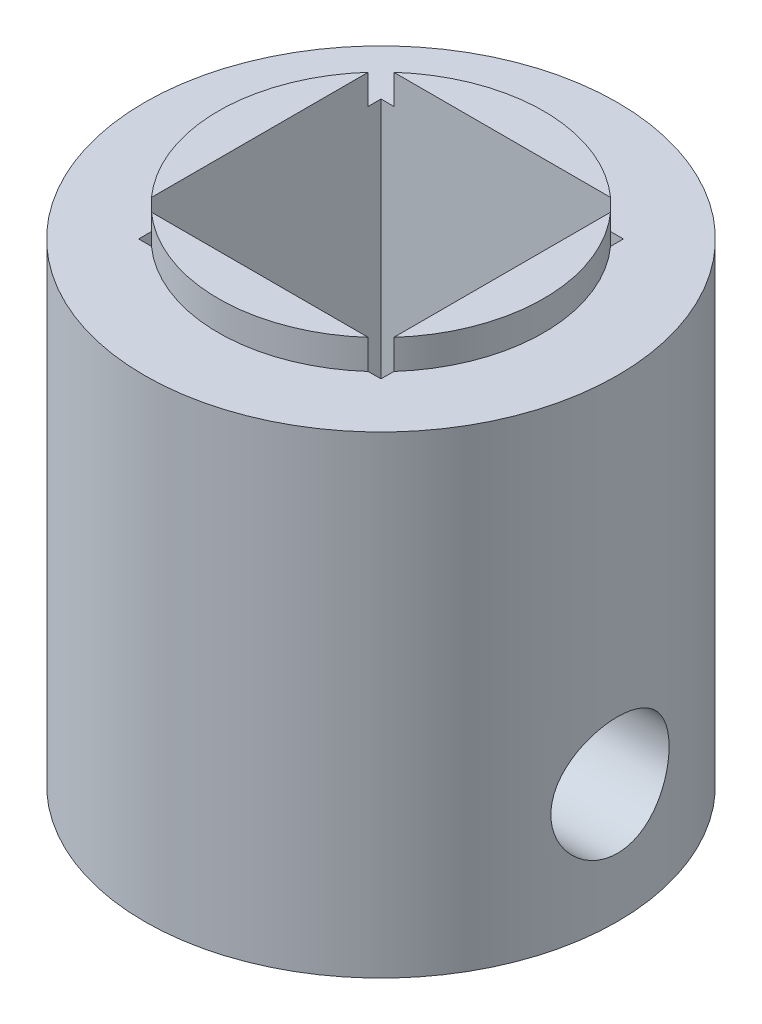
SolidWorks part; units mm, degrees
ref_plane "Front" through (0, 0, 0) normal (0, 0, 1) x (1, 0, 0)
ref_plane "Top" through (0, 0, 0) normal (0, 1, 0) x (1, 0, 0)
ref_plane "Right" through (0, 0, 0) normal (1, 0, 0) x (0, 0, -1)
sketch "Sketch1" plane through (0, 0, 0) normal (0, 1, 0) x (1, 0, 0)
  circle A0 centre (0, 0) radius 5.5
extrude "Boss-Extrude1" add sketch "Sketch1" along normal blind 1
sketch "Sketch2" plane through (0, 0, 0) normal (0, -1, 0) x (-1, 0, 0)
  circle A0 centre (0, 0) radius 8
extrude "Boss-Extrude2" add sketch "Sketch2" along normal blind 16
sketch "Sketch3" plane through (0, -16, 0) normal (0, -1, 0) x (1, 0, 0)
  line L1 (4.1, -4.1) -> (-4.1, -4.1)
  line L2 (4.1, -4.1) -> (4.1, 4.1)
  line L3 (4.1, 4.1) -> (-4.1, 4.1)
  line L4 (-4.1, -4.1) -> (-4.1, 4.1)
  line L5 (4.1, -4.1) -> (-4.1, 4.1) construction
  line L6 (4.1, 4.1) -> (-4.1, -4.1) construction
  point P0 (0, 0)
  dimension "D1" = 8.2
  dimension "D2" = 8.2
extrude "Cut-Extrude1" cut sketch "Sketch3" against normal through all
ref_plane "Plane1" through (-8, 0, 0) normal (-1, 0, 0) x (0, 0, 1)
sketch "Sketch4" plane through (-8, 0, 0) normal (-1, 0, 0) x (0, 0, 1)
  line L0 (0, -4) -> (0, -12)
  line L1 (8, 0) -> (-8, 0) construction
  circle A0 centre (0, -12) radius 2
  circle A1 centre (0, -4) radius 2
  dimension "D1" = 8
  dimension "D2" = 4
extrude "Cut-Extrude2" cut sketch "Sketch4" against normal through all
